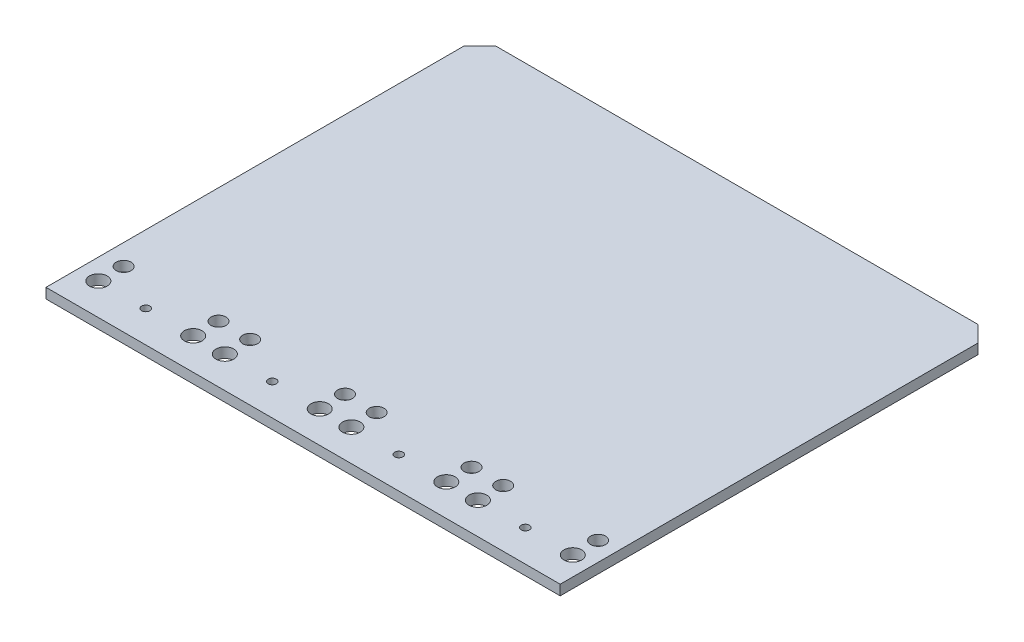
SolidWorks part; units mm, degrees
ref_plane "Front Plane" through (0, 0, 0) normal (0, 0, 1) x (1, 0, 0)
ref_plane "Top Plane" through (0, 0, 0) normal (0, 1, 0) x (1, 0, 0)
ref_plane "Right Plane" through (0, 0, 0) normal (1, 0, 0) x (0, 0, -1)
sketch "Sketch1" plane through (0, 0, 0) normal (0, 1, 0) x (1, 0, 0)
  line L1 (-40.64, 34.29) -> (40.64, 34.29)
  line L2 (-40.64, 34.29) -> (-40.64, -34.29)
  line L3 (-40.64, -34.29) -> (40.64, -34.29)
  line L4 (40.64, 34.29) -> (40.64, -34.29)
  line L5 (-40.64, 34.29) -> (40.64, -34.29) construction
  line L6 (-40.64, -34.29) -> (40.64, 34.29) construction
  point P0 (0, 0)
  dimension "D1" = 81.28
  dimension "D2" = 68.58
extrude "Boss-Extrude1" add sketch "Sketch1" along normal blind 1.6
chamfer "Chamfer1" distance 2.54 angle 45 2 edges at (40.64, 0.8, -34.29) (-40.64, 0.8, -34.29)
sketch "Sketch2" plane through (0, 0, 0) normal (0, -1, 0) x (1, 0, 0)
  line L0 (-29.87, 49.29) -> (-29.87, 20.7568) construction
  line L2 (-45.3779, 25.29) -> (-18.7166, 25.29) construction
  line L3 (-40.64, 34.29) -> (40.64, 34.29) construction
  circle A0 centre (-29.87, 29.29) radius 0.65
  circle A1 centre (-37.37, 29.29) radius 1.4
  circle A2 centre (-22.37, 29.29) radius 1.4
  circle A3 centre (-37.37, 25.29) radius 1.175
  circle A4 centre (-22.37, 25.29) radius 1.175
  dimension "D3" = 1.3
  dimension "D4" = 4
  dimension "D5" = 2.8
  dimension "D6" = 2.8
  dimension "D7" = 7.5
  dimension "D9" = 2.35
  dimension "D10" = 2.35
  dimension "D1" = 29.87
  dimension "D2" = 9
  dimension "D8" = 7.5
extrude "Cut-Extrude1" cut sketch "Sketch2" against normal up to next
pattern_linear "LPattern1" count 4 spacing 20 along (1, 0, 0) of "Cut-Extrude1"
